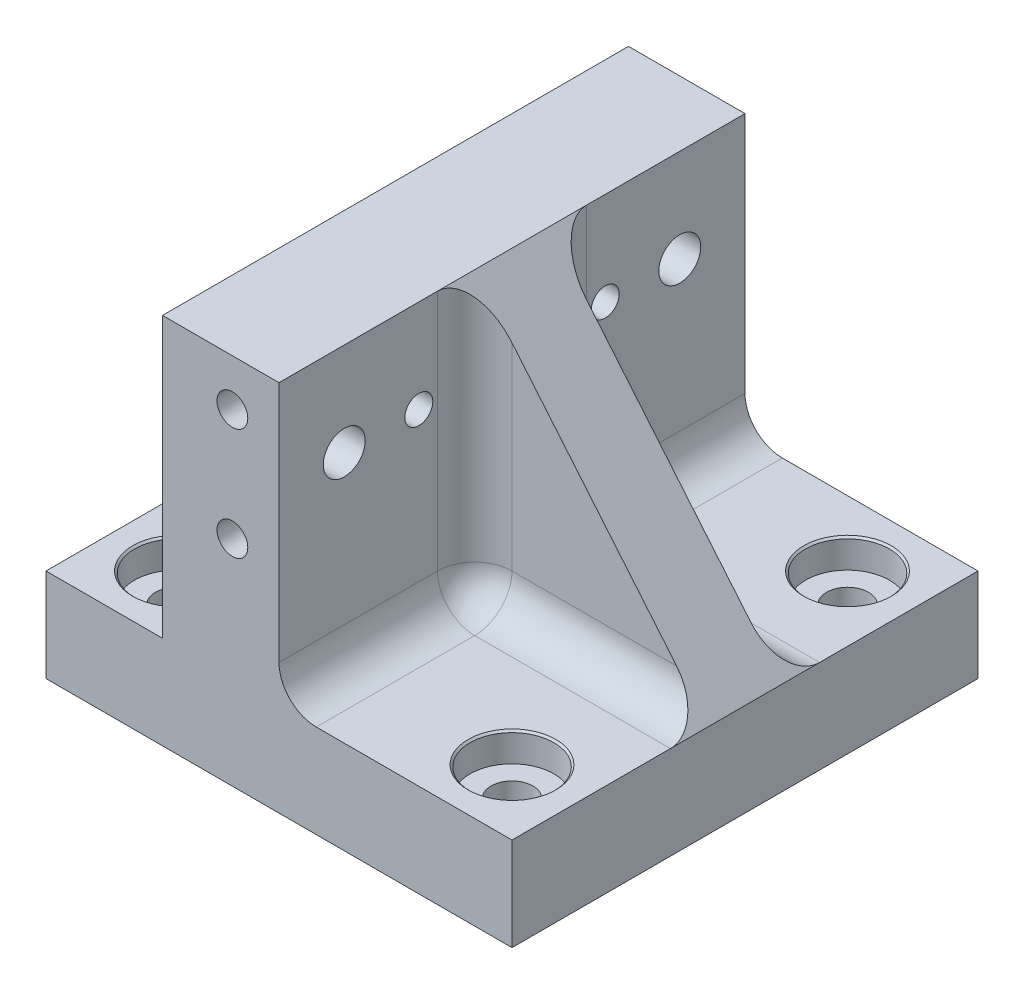
SolidWorks part; units mm, degrees
ref_plane "Front Plane" through (0, 0, 0) normal (0, 0, 1) x (1, 0, 0)
ref_plane "Top Plane" through (0, 0, 0) normal (0, 1, 0) x (1, 0, 0)
ref_plane "Right Plane" through (0, 0, 0) normal (1, 0, 0) x (0, 0, -1)
sketch "Skizze1" plane through (0, 0, 0) normal (0, 1, 0) x (1, 0, 0)
  line L1 (-25, 25) -> (25, 25)
  line L2 (-25, 25) -> (-25, -25)
  line L3 (-25, -25) -> (25, -25)
  line L4 (25, 25) -> (25, -25)
  line L5 (0, -25) -> (0, 25) construction
  line L6 (-25, 0) -> (25, 0) construction
  point P176 (0, 0)
  dimension "D1" = 50
  dimension "D2" = 50
extrude "Aufsatz-Linear austragen1" add sketch "Skizze1" along normal blind 40
sketch "Skizze2" plane through (0, 40, 0) normal (0, 1, 0) x (1, 0, 0)
  line L0 (0, 25) -> (0, -25) construction
  line L1 (25, 25) -> (-25, 25) construction
  line L2 (-25, -25) -> (25, -25) construction
  line L4 (-25, 25) -> (-12.5, 25)
  line L5 (-25, 25) -> (-25, -25)
  line L6 (-25, -25) -> (-12.5, -25)
  line L7 (-12.5, 25) -> (-12.5, -25)
  line L8 (-18.75, -25) -> (-18.75, 25) construction
  line L9 (-25, 0) -> (-12.5, 0) construction
  line L10 (25, 25) -> (0, 25)
  line L11 (25, 25) -> (25, -25)
  line L12 (25, -25) -> (0, -25)
  line L13 (0, 25) -> (0, -25)
  line L14 (12.5, -25) -> (12.5, 25) construction
  line L15 (25, 0) -> (0, 0) construction
  point P642 (-18.75, 0)
  point P972 (12.5, 0)
  dimension "D1" = 12.5
extrude "Schnitt-Linear austragen1" cut sketch "Skizze2" against normal blind 30
hole_wizard "Stirnsenkung für M4 Flachkopfschraube mit Schlitz1" positions "Skizze3" profile "Skizze4" counterbore size "M4" standard "DIN" end condition through all
sketch "Skizze3" plane through (0, 10, 0) normal (0, 1, 0) x (1, 0, 0)
  line L0 (-25, 0) -> (25, 0) construction
  line L1 (-25, 25) -> (-25, -25) construction
  line L2 (25, -25) -> (25, 25) construction
  line L5 (0, 25) -> (0, -25) construction
  point P0 (-18, -18)
  point P20 (-18, 18)
  point P21 (18, -18)
  point P22 (18, 18)
  dimension "D1" = 36
  dimension "D2" = 36
sketch "Skizze4" plane through (-18, 10, 18) normal (1, 0, 0) x (0, 0, 1)
  line L0 (0, 0) -> (0, 10)
  line L1 (0, 10) -> (2.25, 10)
  line L3 (2.25, 10) -> (2.25, 3.1)
  line L4 (4.5, 3.1) -> (2.25, 3.1)
  line L5 (4.5, 3.1) -> (4.5, 0.2)
  line L6 (4.5, 0.2) -> (4.7, 0)
  line L7 (4.7, 0) -> (0, 0)
  line L8 (-4.5, 0.2) -> (-4.7, 0) construction
  line L11 (0, -6.35) -> (0, 107.95) construction
  dimension "Bohrerdurchmesser" = 4.5
  dimension "Bohrungstiefe" = 10
  dimension "Senkdurchmesser2" = 9
  dimension "Senktiefe2" = 3.1
  dimension "Senkdurchmesser4 (Oben)" = 9.4
  dimension "Senkwinkel2 (Oben)" = 90
sketch "Skizze7" plane through (0, 0, 0) normal (0, 0, 1) x (1, 0, 0)
  line L0 (0, 40) -> (25, 10)
rib "Verstärkungsrippe4" sketch "Skizze7" sketch "Skizze7" thickness 8 extrusion direction parallel to sketch draft on no parameters "D1"=8
fillet "Verrundung1" radius 4 6 edges at (0, 25, -4) (0, 25, 4) (0, 10, 14.5) (0, 10, -14.5) (12.5, 10, -4) (12.5, 10, 4)
hole_wizard "Durchgangsloch für M41" positions "Skizze8" profile "Skizze9" hole size "M4" standard "DIN" end condition through all
sketch "Skizze8" plane through (0, 0, 0) normal (1, 0, 0) x (0, 0, -1)
  line L0 (0, 40) -> (0, 0) construction
  line L1 (-8, 40) -> (8, 40) construction
  line L3 (-8, 40) -> (-25, 40) construction
  point P0 (-18, 30)
  point P10 (18, 30)
  dimension "D1" = 36
  dimension "D2" = 10
sketch "Skizze9" plane through (0, 30, 18) normal (0, 1, 0) x (0, 0, -1)
  line L0 (0, 0) -> (0, 25)
  line L1 (0, 25) -> (2.25, 25)
  line L2 (2.25, 25) -> (2.25, 0)
  line L5 (2.25, 0) -> (0, 0)
  line L11 (0, -6.35) -> (0, 107.95) construction
  dimension "Bohrerdurchmesser" = 4.5
  dimension "Bohrungstiefe" = 25
hole_wizard "Ø3.0 (3) Durchmesser Bohrung1" positions "Skizze10" profile "Skizze11" hole size "Ø3.0" standard "DIN" end condition through all
sketch "Skizze10" plane through (-12.5, 0, 0) normal (-1, 0, 0) x (0, 0, 1)
  line L0 (0, 40) -> (0, 0) construction
  line L1 (25, 40) -> (-25, 40) construction
  line L3 (18, 30) -> (-18, 30) construction
  point P0 (-10, 30)
  point P21 (10, 30)
  dimension "D1" = 20
sketch "Skizze11" plane through (-12.5, 30, -10) normal (0, 1, 0) x (0, 0, 1)
  line L0 (0, 0) -> (0, 37.5)
  line L1 (0, 37.5) -> (1.5, 37.5)
  line L2 (1.5, 37.5) -> (1.5, 0)
  line L5 (1.5, 0) -> (0, 0)
  line L11 (0, -6.35) -> (0, 107.95) construction
  dimension "Bohrerdurchmesser" = 3
  dimension "Bohrungstiefe" = 37.5
hole_wizard "M4 Gewindebohrung1" positions "Skizze12" profile "Skizze14" tap size "M4" standard "DIN"
sketch "Skizze12" plane through (0, 0, -25) normal (0, 0, -1) x (-1, 0, 0)
  line L2 (5, 40) -> (5, 0) construction
  line L4 (0, 40) -> (12.5, 40) construction
  line L5 (-25, 0) -> (25, 0) construction
  line L6 (0, 40) -> (0, 14) construction
  point P0 (5, 35)
  point P2 (5, 23)
  dimension "D1" = 5
  dimension "D2" = 12
  dimension "D3" = 5
sketch "Skizze14" plane through (-5, 35, -25) normal (1, 0, 0) x (0, 1, 0)
  line L0 (0, 0) -> (0, 12.4914)
  line L1 (0, 12.4914) -> (1.65, 11.5)
  line L2 (1.65, 11.5) -> (1.65, 0)
  line L5 (1.65, 0) -> (0, 0)
  line L10 (0, 12.4914) -> (-1.65, 11.5) construction
  line L11 (0, -6.35) -> (0, 107.95) construction
  dimension "Bohrerdurchmesser" = 3.3
  dimension "Bohrungstiefe" = 11.5
  dimension "Spitzenwinkel" = 118
cosmetic thread "Bohrungsgewinde1" parameters "D1"=8, "D2"=4
cosmetic thread "Bohrungsgewinde2" parameters "D1"=8, "D2"=4
mirror "Spiegeln1" about plane through (0, 0, 0) normal (0, 0, 1) of "M4 Gewindebohrung1"
